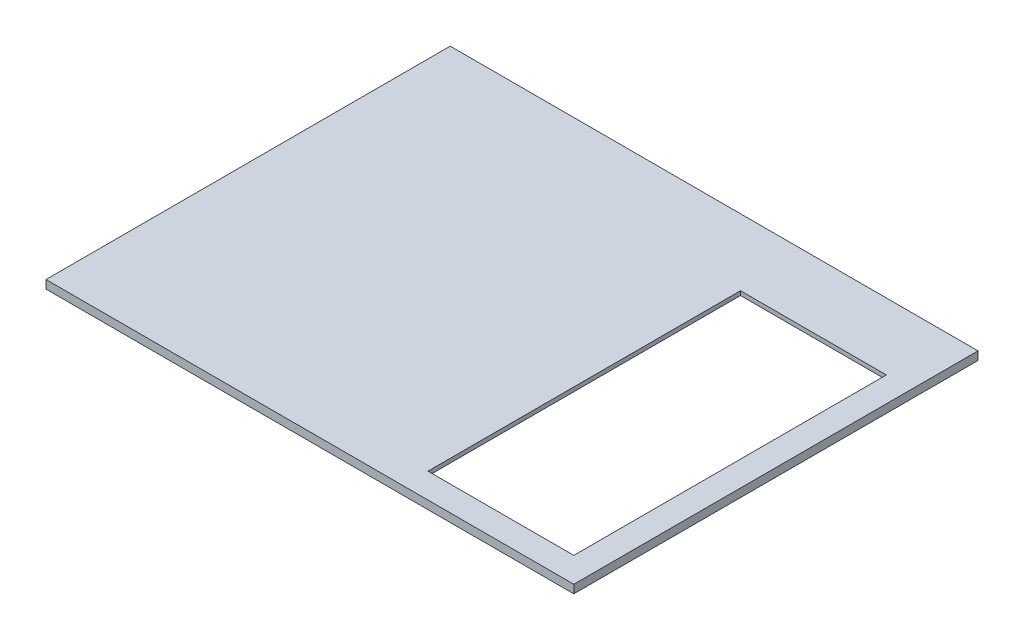
SolidWorks part; units mm, degrees
ref_plane "Спереди" through (0, 0, 0) normal (0, 0, 1) x (1, 0, 0)
ref_plane "Сверху" through (0, 0, 0) normal (0, 1, 0) x (1, 0, 0)
ref_plane "Справа" through (0, 0, 0) normal (1, 0, 0) x (0, 0, -1)
other "Configuration Table"
sketch "Эскиз1" plane through (0, 0, 0) normal (0, 1, 0) x (1, 0, 0)
  line L1 (190, 145.5) -> (-190, 145.5)
  line L2 (190, 145.5) -> (190, -145.5)
  line L3 (190, -145.5) -> (-190, -145.5)
  line L4 (-190, 145.5) -> (-190, -145.5)
  line L5 (190, 145.5) -> (-190, -145.5) construction
  line L6 (190, -145.5) -> (-190, 145.5) construction
  point P0 (0, 0)
  dimension "D1" = 380
  dimension "D2" = 291
extrude "Бобышка-Вытянуть1" add sketch "Эскиз1" along normal blind 3
sketch "Эскиз2" plane through (0, 0, 0) normal (0, -1, 0) x (1, 0, 0)
  line L22 (-172, -127.5) -> (172, -127.5)
  line L23 (-172, -127.5) -> (-172, 127.5)
  line L24 (-172, 127.5) -> (172, 127.5)
  line L25 (172, -127.5) -> (172, 127.5)
  line L26 (-172, -127.5) -> (172, 127.5) construction
  line L27 (-172, 127.5) -> (172, -127.5) construction
  line L28 (-190, -145.5) -> (190, -145.5)
  line L29 (-190, -145.5) -> (-190, 145.5)
  line L30 (-190, 145.5) -> (190, 145.5)
  line L31 (190, -145.5) -> (190, 145.5)
  line L32 (-190, -145.5) -> (190, 145.5) construction
  line L33 (-190, 145.5) -> (190, -145.5) construction
  point P0 (0, 0)
  point P6 (0, 0)
  dimension "D1" = 18
  dimension "D2" = 18
extrude "Бобышка-Вытянуть3" add sketch "Эскиз2" along normal blind 3
sketch "Эскиз7" plane through (0, 0, 0) normal (0, -1, 0) x (1, 0, 0)
  line L1 (172, 127.5) -> (67, 127.5)
  line L2 (172, 127.5) -> (172, -97.5)
  line L3 (172, -97.5) -> (67, -97.5)
  line L4 (67, 127.5) -> (67, -97.5)
  dimension "D1" = 225
  dimension "D2" = 105
extrude "Вырез-Вытянуть1" cut sketch "Эскиз7" against normal blind 3
